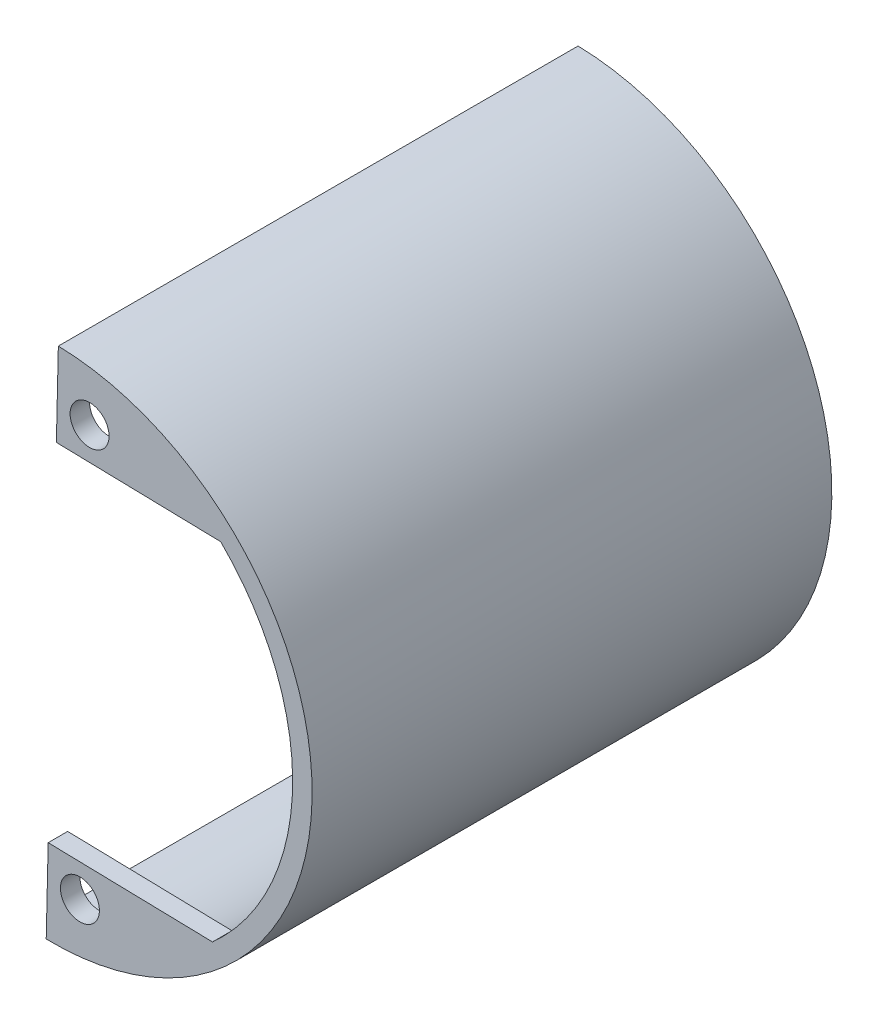
SolidWorks part; units mm, degrees
ref_plane "Front Plane" through (0, 0, 0) normal (0, 0, 1) x (1, 0, 0)
ref_plane "Top Plane" through (0, 0, 0) normal (0, 1, 0) x (1, 0, 0)
ref_plane "Right Plane" through (0, 0, 0) normal (1, 0, 0) x (0, 0, -1)
sketch "Sketch2" plane through (0, 0, 0) normal (0, 0, 1) x (1, 0, 0)
  line L0 (0.8636, 36.9899) -> (0.9336, 39.9891) construction
  line L1 (0.9336, 39.9891) -> (0.8636, 36.9899) construction
  line L2 (0.9336, 39.9891) -> (0.8636, 36.9899)
  line L3 (-0.8636, -36.9899) -> (-0.9336, -39.9891)
  arc A0 (-0.9336, -39.9891) -> (0.9336, 39.9891) centre (0, 0) ccw
  arc A1 (-0.8636, -36.9899) -> (0.8636, 36.9899) centre (0, 0) ccw
  dimension "D2" = 74
  dimension "D1" = 80
extrude "Boss-Extrude1" add sketch "Sketch2" along normal blind 80
ref_plane "Plane1" through (0.8636, 36.9899, 80) normal (0.9997, -0.0233, 0) x (0, 0, -1)
sketch "Sketch4" plane through (0, 0, 0) normal (-0.9997, 0.0233, 0) x (0, 0, 1)
  line L0 (80, -37) -> (80, -27)
  line L1 (80, -27) -> (77, -27)
  line L2 (77, -27) -> (77, -37)
  line L3 (80, -37) -> (0, -37) construction
  line L4 (77, -37) -> (80, -37)
  dimension "D1" = 10
  dimension "D2" = 3
extrude "Boss-Extrude2" add sketch "Sketch4" against normal up to surface (25.2982 mm away)
sketch "Sketch5" plane through (0, 0, 0) normal (-0.9997, 0.0233, 0) x (0, 0, 1)
  line L0 (80, 37) -> (80, 27)
  line L1 (80, 27) -> (77, 27)
  line L2 (77, 27) -> (77, 37)
  line L3 (80, 37) -> (0, 37) construction
  line L4 (77, 37) -> (80, 37)
  dimension "D1" = 10
  dimension "D2" = 3
extrude "Boss-Extrude3" add sketch "Sketch5" against normal up to surface up to face at (18.1939, -8.3949, 52.3333)
sketch "Sketch6" plane through (0, 0, 77) normal (0, 0, -1) x (-1, 0, 0)
  line L0 (-25.9215, 26.4022) -> (-0.6302, 26.9926) construction
  line L1 (-1.2391, 53.0767) -> (-0.488, 20.9032) construction
  line L2 (0.6302, -26.9926) -> (0.8636, -36.9899) construction
  line L3 (-24.6612, -27.5831) -> (0.6302, -26.9926) construction
  circle A0 centre (-5.7455, 31.8746) radius 3
  circle A1 centre (-4.2518, -32.108) radius 3
  dimension "D1" = 6
  dimension "D2" = 6
  dimension "D3" = 5
  dimension "D4" = 5
  dimension "D5" = 5
  dimension "D6" = 5
extrude "Cut-Extrude1" cut sketch "Sketch6" against normal up to surface (3 mm away) up to face at (17.0451, -0.3979, 80)
